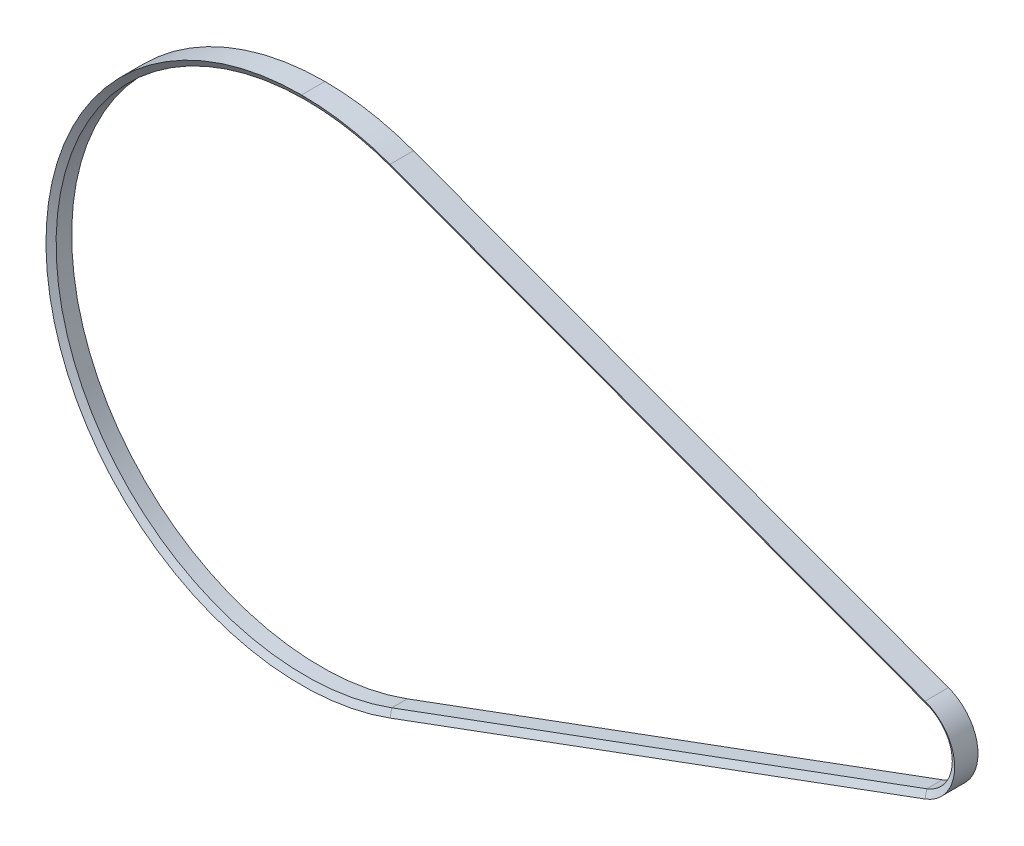
SolidWorks part; units mm, degrees
ref_plane "Front Plane" through (0, 0, 0) normal (0, 0, 1) x (1, 0, 0)
ref_plane "Top Plane" through (0, 0, 0) normal (0, 1, 0) x (1, 0, 0)
ref_plane "Right Plane" through (0, 0, 0) normal (1, 0, 0) x (0, 0, -1)
sketch "Sketch1" plane through (0, 0, 0) normal (0, 0, 1) x (1, 0, 0)
  line L0 (0, 0) -> (495.3, 0) construction
  line L1 (70.3385, 190.6377) -> (506.2904, 29.7871)
  line L2 (70.3385, -190.6377) -> (506.2904, -29.7871)
  arc A0 (70.3385, 190.6377) -> (70.3385, -190.6377) centre (0, 0) ccw
  arc A1 (506.2904, -29.7871) -> (506.2904, 29.7871) centre (495.3, 0) ccw
  point P1 (0, 203.2)
  dimension "D1" = 406.4
  dimension "D2" = 63.5
  dimension "D3" = 495.3
sketch "Sketch3" plane through (0, 0, 0) normal (1, 0, 0) x (0, 0, -1)
  line L0 (0, 208.28) -> (0, 203.2) construction
  line L1 (-6.35, 203.2) -> (6.35, 203.2)
  line L2 (-9.525, 208.28) -> (9.525, 208.28)
  line L3 (9.525, 208.28) -> (6.35, 203.2)
  line L4 (-9.525, 208.28) -> (-6.35, 203.2)
  dimension "D1" = 9.525
  dimension "D2" = 6.35
  dimension "D3" = 5.08
sweep "Sweep1" add profiles "Sketch3" path "Sketch1"
